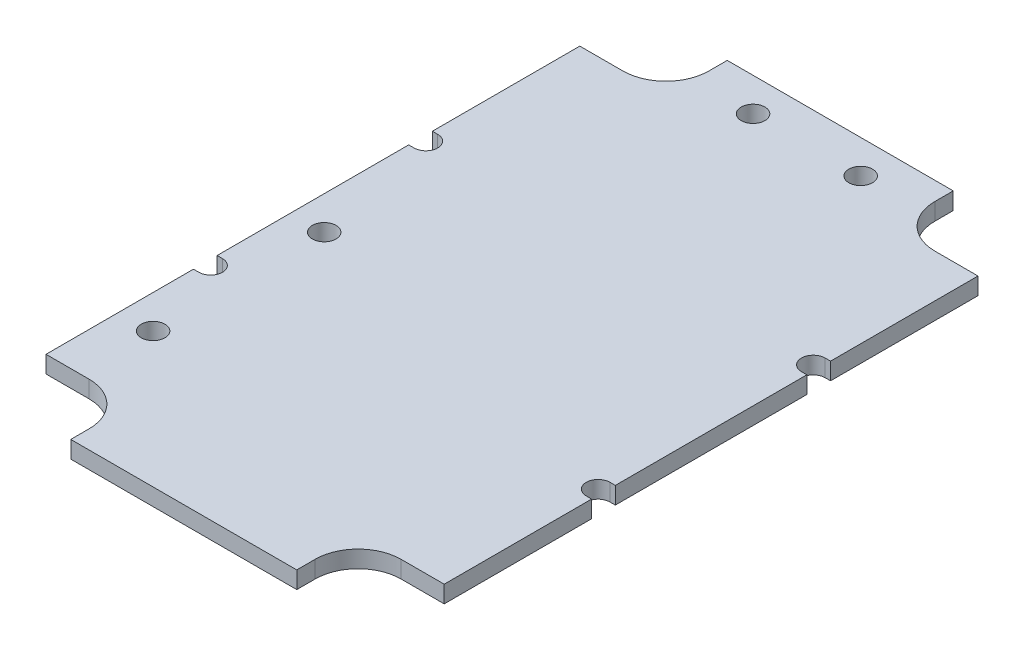
SolidWorks part; units mm, degrees
material "E-Glass Fiber"
ref_plane "Front Plane" through (0, 0, 0) normal (0, 0, 1) x (1, 0, 0)
ref_plane "Top Plane" through (0, 0, 0) normal (0, 1, 0) x (1, 0, 0)
ref_plane "Right Plane" through (0, 0, 0) normal (1, 0, 0) x (0, 0, -1)
sketch "Sketch1" plane through (0, 0, 0) normal (0, 1, 0) x (1, 0, 0)
  line L1 (18.5, -30.5) -> (-18.5, -30.5)
  line L2 (18.5, -30.5) -> (18.5, 30.5)
  line L3 (18.5, 30.5) -> (-18.5, 30.5)
  line L4 (-18.5, -30.5) -> (-18.5, 30.5)
  line L5 (18.5, -30.5) -> (-18.5, 30.5) construction
  line L6 (18.5, 30.5) -> (-18.5, -30.5) construction
  point P0 (0, 0)
  dimension "D1" = 37
  dimension "D2" = 61
extrude "Base Extrusion" add sketch "Sketch1" along normal blind 1.5875
chamfer "Corner Chamfer" [suppressed] distance 7 angle 45
hole_wizard "M2 Clearance Hole3" positions "Sketch6" profile "Sketch5" hole size "M2" standard "ANSI Metric" end condition through all
sketch "Sketch6" plane through (0, 1.5875, 0) normal (0, 1, 0) x (1, 0, 0)
  line L0 (-0.8731, 0) -> (0.8731, 0) construction
  line L1 (0, -0.8731) -> (0, 0.8731) construction
  line L2 (-18, 10) -> (18, 10) construction
  line L5 (-18, 10) -> (-18, -10) construction
  point P0 (-18, 10)
  point P2 (-18, -10)
  point P4 (18, -10)
  point P6 (18, 10)
  point P26 (-18, 0)
  point P27 (0, 10)
  dimension "D1" = 10
  dimension "D2" = 18
sketch "Sketch5" plane through (-18, 1.5875, -10) normal (1, 0, 0) x (0, 0, 1)
  line L0 (0, 0) -> (0, 1.5875)
  line L1 (0, 1.5875) -> (1.1, 1.5875)
  line L2 (1.1, 1.5875) -> (1.1, 0)
  line L5 (1.1, 0) -> (0, 0)
  line L11 (0, -6.35) -> (0, 107.95) construction
  dimension "Thru Hole Dia." = 2.2
  dimension "Thru Hole Depth" = 1.5875
sketch "Sketch8" plane through (0, 1.5875, 0) normal (0, 1, 0) x (1, 0, 0)
  line L0 (-18.5, 9.0202) -> (-18.5, -9.0202) construction
  line L1 (-18, 11.1) -> (-18.5, 11.1)
  line L2 (-18, 11.1) -> (-18, 8.9)
  line L3 (-18, 8.9) -> (-18.5, 8.9)
  line L4 (-18.5, 11.1) -> (-18.5, 8.9)
  line L5 (-18.5, -10.9798) -> (-18.5, -30.5) construction
  line L6 (-18, -8.9) -> (-18.5, -8.9)
  line L7 (-18, -8.9) -> (-18, -11.1)
  line L8 (-18, -11.1) -> (-18.5, -11.1)
  line L9 (-18.5, -8.9) -> (-18.5, -11.1)
  line L10 (18.5, -9.0202) -> (18.5, 9.0202) construction
  line L11 (18, 11.1) -> (18.5, 11.1)
  line L12 (18, 11.1) -> (18, 8.9)
  line L13 (18, 8.9) -> (18.5, 8.9)
  line L14 (18.5, 11.1) -> (18.5, 8.9)
  line L15 (18.5, -30.5) -> (18.5, -10.9798) construction
  line L16 (18, -8.9) -> (18.5, -8.9)
  line L17 (18, -8.9) -> (18, -11.1)
  line L18 (18, -11.1) -> (18.5, -11.1)
  line L19 (18.5, -8.9) -> (18.5, -11.1)
  arc A0 (-18.5, 9.0202) -> (-18.5, 10.9798) centre (-18, 10) ccw construction
  arc A1 (-18.5, -10.9798) -> (-18.5, -9.0202) centre (-18, -10) ccw construction
  arc A2 (18.5, 10.9798) -> (18.5, 9.0202) centre (18, 10) ccw construction
  arc A3 (18.5, -9.0202) -> (18.5, -10.9798) centre (18, -10) ccw construction
extrude "Side Slots" cut sketch "Sketch8" against normal through all
sketch "Sketch7" plane through (0, 1.5875, 0) normal (0, 1, 0) x (1, 0, 0)
  circle A0 centre (0, 0) radius 2.125
  dimension "D1" = 4.25
extrude "Central Hole" [suppressed] cut sketch "Sketch7" against normal through all
sketch "Sketch9" plane through (0, 1.5875, 0) normal (0, 1, 0) x (1, 0, 0)
  line L0 (0, -0.8731) -> (0, 0.8731) construction
  line L2 (-0.8731, 0) -> (0.8731, 0) construction
  line L3 (-18.5, -32.8) -> (-10.5, -32.8)
  line L4 (-10.5, -32.8) -> (-10.5, -28.8)
  line L5 (-14.5, -24.8) -> (-18.5, -24.8)
  line L6 (-18.5, -24.8) -> (-18.5, -32.8)
  line L7 (-18.5, -11.1) -> (-18.5, -30.5) construction
  circle A0 centre (-14.5, -28.8) radius 4 construction
  arc A1 (-10.5, -28.8) -> (-14.5, -24.8) centre (-14.5, -28.8) ccw
  dimension "D1" = 14.5
  dimension "D3" = 8
  dimension "D2" = 28.8
extrude "Corner Boss Clearance" cut sketch "Sketch9" against normal through all
mirror "Corner Boss Clearance Mirror" about plane through (0, 0, 0) normal (1, 0, 0) of "Corner Boss Clearance"
mirror "Corner Boss Clearance Mirror 2" about plane through (0, 0, 0) normal (0, 0, 1) of "Corner Boss Clearance Mirror", "Corner Boss Clearance"
sketch "Sketch10" plane through (0, 0, 0) normal (0, -1, 0) x (1, 0, 0)
  line L0 (-5, -27.4) -> (5, -27.4) construction
  line L1 (0, -0.8731) -> (0, 0.8731) construction
  line L2 (-15.4, 17.95) -> (-15.4, 2.05) construction
  line L3 (10.5, -30.5) -> (-10.5, -30.5) construction
  line L4 (-18, 10) -> (-15.4, 10) construction
  line L6 (-15.4, 17.95) -> (15.4, 17.95) construction
  line L7 (-18.5, 11.1) -> (-18.5, 24.8) construction
  circle A0 centre (-5, -27.4) radius 1.1
  circle A1 centre (5, -27.4) radius 1.1
  circle A2 centre (-5, -27.4) radius 3.1 construction
  circle A3 centre (-15.4, 17.95) radius 1.1
  circle A4 centre (-15.4, 17.95) radius 3.1 construction
  circle A5 centre (15.4, 17.95) radius 1.1 construction
  circle A6 centre (-15.4, 2.05) radius 1.1
  point P3 (0, -27.4)
  point P17 (0, 17.95)
  point P25 (-18.5, 17.95)
  dimension "D1" = 2.2
  dimension "D2" = 2
  dimension "D3" = 10
extrude "AC Wire Holes" cut sketch "Sketch10" against normal through all
